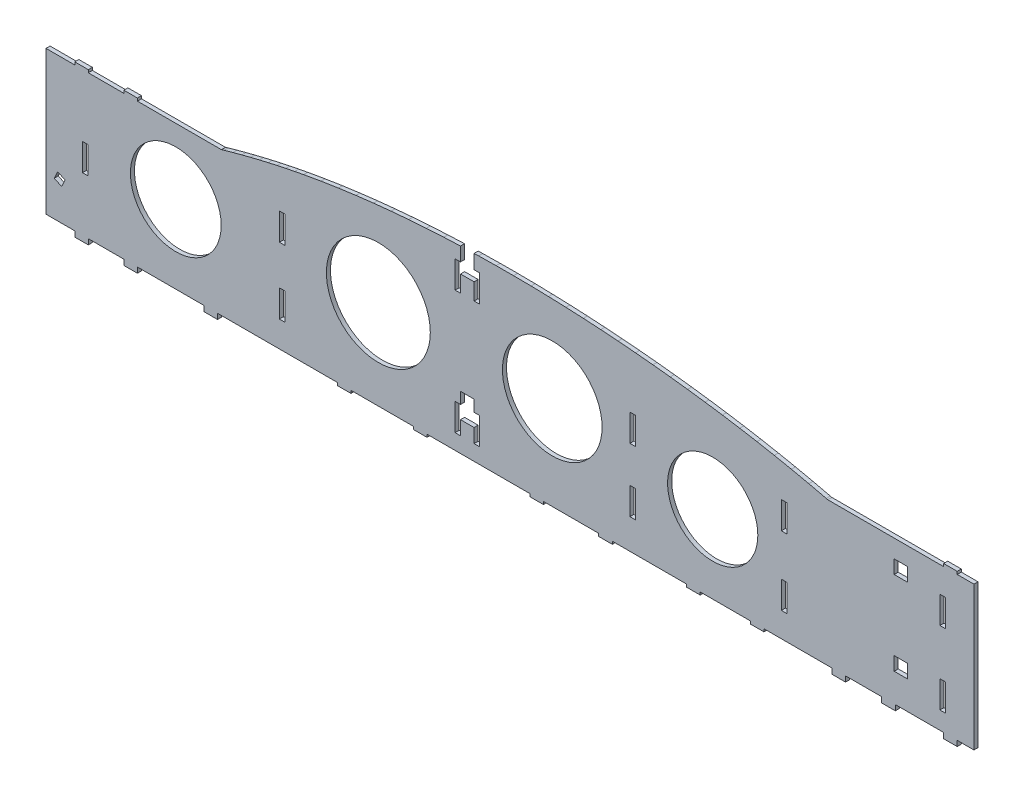
SolidWorks part; units mm, degrees
ref_plane "前视基准面" through (0, 0, 0) normal (0, 0, 1) x (1, 0, 0)
ref_plane "上视基准面" through (0, 0, 0) normal (0, 1, 0) x (1, 0, 0)
ref_plane "右视基准面" through (0, 0, 0) normal (1, 0, 0) x (0, 0, -1)
sketch "Model" plane through (0, 0, 0) normal (0, 0, 1) x (1, 0, 0)
  line L0 (331.0085, -12.6811) -> (341.6164, -12.6811)
  line L1 (346.6164, -12.6811) -> (359.7315, -12.6811)
  line L2 (364.7315, -12.6811) -> (389.2851, -12.6811)
  line L3 (394.2851, -12.6811) -> (438.5273, -12.6811)
  line L4 (443.5273, -12.6811) -> (466.5951, -12.6811)
  line L5 (471.5951, -12.6811) -> (509.5438, -12.6811)
  line L6 (514.5438, -12.6811) -> (534.9411, -12.6811)
  line L7 (539.9411, -12.6811) -> (567.3932, -12.6811)
  line L8 (572.3932, -12.6811) -> (590.9092, -12.6811)
  line L9 (595.9092, -12.6811) -> (621.0096, -12.6811)
  line L10 (334.0546, 0.3468) -> (335.3495, 3.053)
  line L11 (335.3495, 3.053) -> (338.0557, 1.7581)
  line L12 (338.0557, 1.7581) -> (336.7608, -0.9481)
  line L13 (336.7608, -0.9481) -> (334.0546, 0.3468)
  line L14 (488.9439, 7.2129) -> (483.9439, 7.2129)
  line L15 (483.9439, 7.2129) -> (483.9439, 3.0018)
  line L16 (331.0085, 40.3189) -> (341.6164, 40.3189)
  line L17 (346.6164, 40.3189) -> (359.7315, 40.3189)
  line L18 (626.0096, -12.6811) -> (639.3521, -12.6811)
  line L19 (644.3521, -12.6811) -> (662.2037, -12.6811)
  line L20 (667.2037, -12.6811) -> (673.3752, -12.6811)
  line L21 (364.7315, 40.3189) -> (395.7536, 40.3189)
  line L22 (619.4612, 40.3189) -> (662.2037, 40.3189)
  line L23 (667.2037, 40.3189) -> (673.3752, 40.3189)
  line L24 (673.3752, 40.3189) -> (673.3752, -12.6811)
  line L25 (331.0085, 40.3189) -> (331.0085, -12.6811)
  line L26 (419.1049, 6.8765) -> (417.1049, 6.8765)
  line L27 (419.1049, -3.1235) -> (417.1049, -3.1235)
  line L28 (548.4377, 8.4018) -> (546.4377, 8.4018)
  line L29 (548.4377, -1.5982) -> (546.4377, -1.5982)
  line L30 (604.3756, -3.6213) -> (602.3131, -3.6213)
  line L31 (483.9439, 3.0018) -> (481.9439, 3.0018)
  line L32 (344.4474, 17.3189) -> (346.4474, 17.3189)
  line L33 (344.4474, 7.3189) -> (346.4474, 7.3189)
  line L34 (419.1049, 31.4267) -> (417.1049, 31.4267)
  line L35 (419.1049, 21.4267) -> (417.1049, 21.4267)
  line L36 (483.9439, 48.5508) -> (481.9439, 48.5508)
  line L37 (483.9439, 38.5508) -> (481.9439, 38.5508)
  line L38 (548.4377, 31.8236) -> (546.4377, 31.8236)
  line L39 (548.4377, 21.8236) -> (546.4377, 21.8236)
  line L40 (604.3131, 21.8236) -> (602.3131, 21.8236)
  line L41 (346.4474, 17.3189) -> (346.4474, 7.3189)
  line L42 (344.4474, 17.3189) -> (344.4474, 7.3189)
  line L43 (419.1049, 31.4267) -> (419.1049, 21.4267)
  line L44 (417.1049, 31.4267) -> (417.1049, 21.4267)
  line L45 (419.1049, 6.8765) -> (419.1049, -3.1235)
  line L46 (417.1049, 6.8765) -> (417.1049, -3.1235)
  line L47 (481.9439, 48.5508) -> (481.9439, 38.5508)
  line L48 (483.9439, 44.7013) -> (483.9439, 38.5508)
  line L49 (481.9439, 3.0018) -> (481.9439, -6.9982)
  line L50 (481.9439, -6.9982) -> (483.9439, -6.9982)
  line L51 (483.9439, -6.9982) -> (483.9439, -1.8508)
  line L52 (546.4377, 31.8236) -> (546.4377, 21.8236)
  line L53 (548.4377, 21.8236) -> (548.4377, 31.8236)
  line L54 (546.4377, 8.4018) -> (546.4377, -1.5982)
  line L55 (548.4377, -1.5982) -> (548.4377, 8.4018)
  line L56 (483.9439, 53.6243) -> (483.9439, 48.5508)
  line L57 (341.6164, 40.3189) -> (341.6164, 41.3189)
  line L58 (341.6164, 41.3189) -> (346.6164, 41.3189)
  line L59 (359.7315, 41.3189) -> (364.7315, 41.3189)
  line L60 (346.6164, 40.3189) -> (346.6164, 41.3189)
  line L61 (359.7315, 40.3189) -> (359.7315, 41.3189)
  line L62 (364.7315, 40.3189) -> (364.7315, 41.3189)
  line L63 (341.6164, -12.6811) -> (341.6164, -14.6811)
  line L64 (341.6164, -14.6811) -> (346.6164, -14.6811)
  line L65 (346.6164, -12.6811) -> (346.6164, -14.6811)
  line L66 (359.7315, -12.6811) -> (359.7315, -14.6811)
  line L67 (359.7315, -14.6811) -> (364.7315, -14.6811)
  line L68 (364.7315, -12.6811) -> (364.7315, -14.6811)
  line L69 (662.2037, 40.3189) -> (662.2037, 41.3189)
  line L70 (662.2037, 41.3189) -> (667.2037, 41.3189)
  line L71 (667.2037, 40.3189) -> (667.2037, 41.3189)
  line L72 (662.2037, -12.6811) -> (662.2037, -14.6811)
  line L73 (662.2037, -14.6811) -> (667.2037, -14.6811)
  line L74 (667.2037, -12.6811) -> (667.2037, -14.6811)
  line L75 (639.3521, -12.6811) -> (639.3521, -14.6811)
  line L76 (639.3521, -14.6811) -> (644.3521, -14.6811)
  line L77 (644.3521, -12.6811) -> (644.3521, -14.6811)
  line L78 (621.0096, -12.6811) -> (621.0096, -14.6811)
  line L79 (621.0096, -14.6811) -> (626.0096, -14.6811)
  line L80 (626.0096, -12.6811) -> (626.0096, -14.6811)
  line L81 (590.9092, -12.6811) -> (590.9092, -13.6811)
  line L82 (590.9092, -13.6811) -> (595.9092, -13.6811)
  line L83 (595.9092, -12.6811) -> (595.9092, -13.6811)
  line L84 (567.3932, -12.6811) -> (567.3932, -13.6811)
  line L85 (567.3932, -13.6811) -> (572.3932, -13.6811)
  line L86 (572.3932, -12.6811) -> (572.3932, -13.6811)
  line L87 (534.9411, -12.6811) -> (534.9411, -13.6811)
  line L88 (534.9411, -13.6811) -> (539.9411, -13.6811)
  line L89 (539.9411, -12.6811) -> (539.9411, -13.6811)
  line L90 (509.5438, -12.6811) -> (509.5438, -13.6811)
  line L91 (509.5438, -13.6811) -> (514.5438, -13.6811)
  line L92 (514.5438, -12.6811) -> (514.5438, -13.6811)
  line L93 (466.5951, -12.6811) -> (466.5951, -13.6811)
  line L94 (466.5951, -13.6811) -> (471.5951, -13.6811)
  line L95 (471.5951, -12.6811) -> (471.5951, -13.6811)
  line L96 (438.5273, -12.6811) -> (438.5273, -13.6811)
  line L97 (438.5273, -13.6811) -> (443.5273, -13.6811)
  line L98 (443.5273, -12.6811) -> (443.5273, -13.6811)
  line L99 (389.2851, -12.6811) -> (389.2851, -14.6811)
  line L100 (389.2851, -14.6811) -> (394.2851, -14.6811)
  line L101 (394.2851, -12.6811) -> (394.2851, -14.6811)
  line L102 (604.3756, 6.3787) -> (602.3131, 6.3787)
  line L103 (662.8241, 20.8189) -> (660.8241, 20.8189)
  line L104 (662.8241, 30.8189) -> (660.8241, 30.8189)
  line L105 (662.8241, 3.8189) -> (660.8241, 3.8189)
  line L106 (662.8241, -6.1811) -> (660.8241, -6.1811)
  line L107 (604.3131, 31.8236) -> (602.3131, 31.8236)
  line L108 (602.3131, 31.8236) -> (602.3131, 21.8236)
  line L109 (604.3131, 21.8236) -> (604.3131, 31.8236)
  line L110 (602.3131, 6.3787) -> (602.3131, -3.6213)
  line L111 (604.3756, -3.6213) -> (604.3756, 6.3787)
  line L112 (662.8241, 30.8189) -> (662.8241, 20.8189)
  line L113 (660.8241, 20.8189) -> (660.8241, 30.8189)
  line L114 (662.8241, 3.8189) -> (662.8241, -6.1811)
  line L115 (660.8241, 3.8189) -> (660.8241, -6.1811)
  line L116 (643.9439, 33.6689) -> (643.9439, 28.6689)
  line L117 (643.9439, 28.6689) -> (648.9439, 28.6689)
  line L118 (643.9439, 2.7598) -> (648.9439, 2.7598)
  line L119 (643.9439, 2.7598) -> (643.9439, -2.2402)
  line L120 (643.9439, -2.2402) -> (648.9439, -2.2402)
  line L121 (648.9439, -2.2402) -> (648.9439, 2.7598)
  line L122 (643.9439, 33.6689) -> (648.9439, 33.6689)
  line L123 (648.9439, 33.6689) -> (648.9439, 28.6689)
  line L124 (619.4612, 40.3189) -> (618.88, 40.4633)
  line L125 (618.88, 40.4633) -> (612.47, 41.9553)
  line L126 (612.47, 41.9553) -> (606.0368, 43.3522)
  line L127 (606.0368, 43.3522) -> (599.6896, 44.6333)
  line L128 (599.6896, 44.6333) -> (593.3274, 45.822)
  line L129 (593.3274, 45.822) -> (586.9493, 46.9212)
  line L130 (586.9493, 46.9212) -> (580.5575, 47.936)
  line L131 (580.5575, 47.936) -> (574.152, 48.8663)
  line L132 (574.152, 48.8663) -> (567.7349, 49.716)
  line L133 (567.7349, 49.716) -> (561.3055, 50.4882)
  line L134 (561.3055, 50.4882) -> (554.9076, 51.1809)
  line L135 (554.9076, 51.1809) -> (548.5034, 51.7978)
  line L136 (548.5034, 51.7978) -> (542.0939, 52.3389)
  line L137 (542.0939, 52.3389) -> (535.6801, 52.8031)
  line L138 (535.6801, 52.8031) -> (529.2598, 53.1896)
  line L139 (529.2598, 53.1896) -> (522.8341, 53.4981)
  line L140 (522.8341, 53.4981) -> (516.404, 53.7268)
  line L141 (516.404, 53.7268) -> (509.9624, 53.8759)
  line L142 (509.9624, 53.8759) -> (503.5212, 53.943)
  line L143 (503.5212, 53.943) -> (497.0803, 53.9259)
  line L144 (497.0803, 53.9259) -> (490.6398, 53.8247)
  line L145 (490.6398, 53.8247) -> (488.9439, 53.7749)
  line L146 (483.9439, 53.6243) -> (477.7642, 53.3589)
  line L147 (477.7642, 53.3589) -> (471.329, 52.9903)
  line L148 (471.329, 52.9903) -> (464.8225, 52.5246)
  line L149 (464.8225, 52.5246) -> (458.3256, 51.9595)
  line L150 (458.3256, 51.9595) -> (451.8393, 51.2918)
  line L151 (451.8393, 51.2918) -> (445.3664, 50.5174)
  line L152 (445.3664, 50.5174) -> (438.9085, 49.6292)
  line L153 (438.9085, 49.6292) -> (432.4675, 48.6242)
  line L154 (432.4675, 48.6242) -> (426.0463, 47.4982)
  line L155 (426.0463, 47.4982) -> (422.775, 46.8743)
  line L156 (422.775, 46.8743) -> (419.5102, 46.2171)
  line L157 (419.5102, 46.2171) -> (416.253, 45.5275)
  line L158 (416.253, 45.5275) -> (413.0043, 44.8026)
  line L159 (413.0043, 44.8026) -> (409.7622, 44.0443)
  line L160 (409.7622, 44.0443) -> (406.5285, 43.2506)
  line L161 (406.5285, 43.2506) -> (403.3032, 42.4205)
  line L162 (403.3032, 42.4205) -> (400.0003, 41.5317)
  line L163 (400.0003, 41.5317) -> (396.7096, 40.6023)
  line L164 (396.7096, 40.6023) -> (395.7536, 40.3189)
  line L165 (488.9439, 38.5508) -> (490.9439, 38.5508)
  line L166 (488.9439, 3.0018) -> (490.9439, 3.0018)
  line L167 (490.9439, -6.9982) -> (488.9439, -6.9982)
  line L168 (488.9439, 7.2129) -> (488.9439, 3.0018)
  line L169 (490.9439, 3.0018) -> (490.9439, -6.9982)
  line L170 (488.9439, -1.8508) -> (488.9439, -6.9982)
  line L171 (483.9439, -1.8508) -> (488.9439, -1.8508)
  line L172 (488.9439, 44.7013) -> (488.9439, 38.5508)
  line L173 (490.9439, 38.5508) -> (490.9439, 48.5508)
  line L174 (488.9439, 48.5508) -> (488.9439, 53.7749)
  line L175 (483.9439, 44.7013) -> (488.9439, 44.7013)
  line L176 (488.9439, 48.5508) -> (490.9439, 48.5508)
  circle A0 centre (453.6286, 20.4163) radius 19.1667
  circle A1 centre (517.7962, 21.864) radius 18.3853
  circle A2 centre (576.9959, 16.073) radius 16.64
  circle A3 centre (378.8902, 16.0489) radius 16.7528
extrude "凸台-拉伸1" add sketch "Model" along normal blind 1.5
